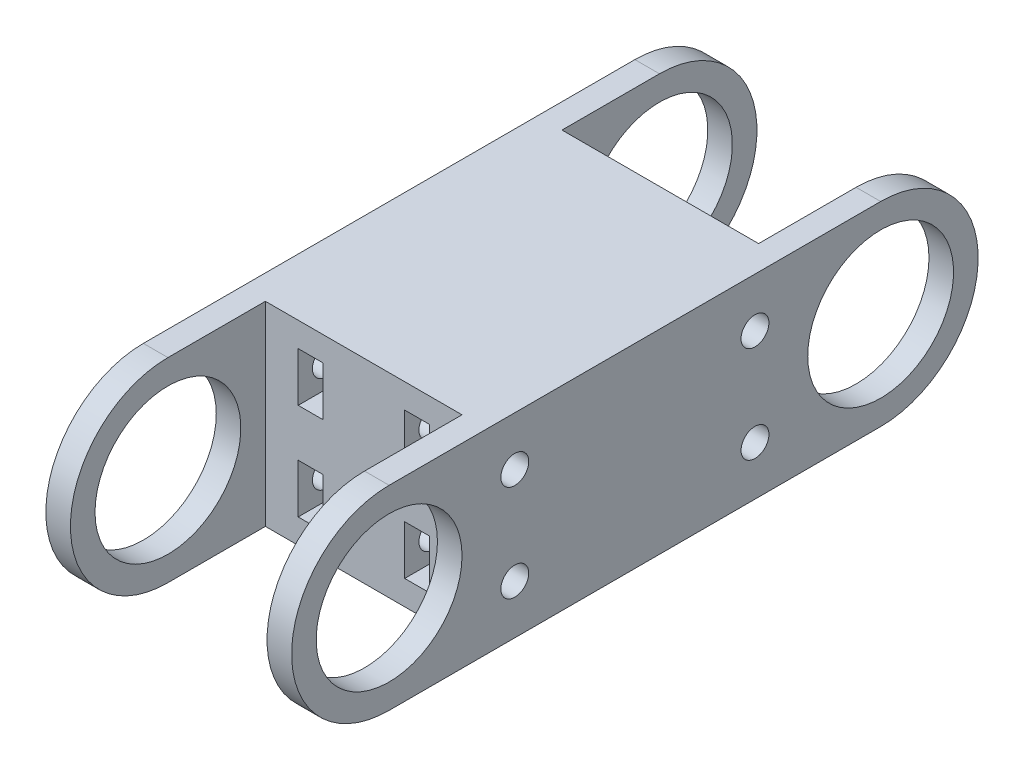
SolidWorks part; units mm, degrees
ref_plane "Front Plane" through (0, 0, 0) normal (0, 0, 1) x (1, 0, 0)
ref_plane "Top Plane" through (0, 0, 0) normal (0, 1, 0) x (1, 0, 0)
ref_plane "Right Plane" through (0, 0, 0) normal (1, 0, 0) x (0, 0, -1)
sketch "Sketch1" plane through (0, 0, 0) normal (1, 0, 0) x (0, 0, -1)
  line L0 (0, 11.9) -> (60, 11.9)
  line L1 (0, -11.9) -> (60, -11.9)
  line L2 (30, 11.9) -> (30, -11.9) construction
  circle A0 centre (0, 0) radius 8.9
  arc A1 (0, 11.9) -> (0, -11.9) centre (0, 0) ccw
  circle A2 centre (60, 0) radius 8.9
  arc A3 (60, 11.9) -> (60, -11.9) centre (60, 0) cw
  point P13 (63.6944, 11.9)
  dimension "D1" = 17.8
  dimension "D2" = 23.8
  dimension "D3" = 60
extrude "Boss-Extrude1" add sketch "Sketch1" along normal blind 30
sketch "Sketch2" plane through (0, 11.9, 0) normal (0, 1, 0) x (1, 0, 0)
  line L0 (0, -11.9) -> (30, -11.9) construction
  line L1 (3, -11.9) -> (27, -11.9)
  line L2 (3, -11.9) -> (3, 11.9)
  line L3 (3, 11.9) -> (27, 11.9)
  line L4 (27, -11.9) -> (27, 11.9)
  line L5 (0, 30) -> (30, 30) construction
  line L6 (0, 60) -> (0, 0) construction
  line L7 (30, 60) -> (30, 0) construction
  line L8 (3, 48.1) -> (27, 48.1)
  line L9 (27, 71.9) -> (27, 48.1)
  line L10 (3, 71.9) -> (27, 71.9)
  line L11 (3, 71.9) -> (3, 48.1)
  dimension "D1" = 23.8
  dimension "D2" = 3
  dimension "D3" = 3
extrude "Cut-Extrude1" cut sketch "Sketch2" against normal through all
hole_wizard "M3 Clearance Hole1" positions "3DSketch1" profile "Sketch3" hole size "M3" standard "ANSI Metric" end condition through all
sketch3d "3DSketch1"
  circle A0 centre (32.975, -5.9, -15.34) radius 1.7 construction
  circle A1 centre (32.975, 5.9, -15.34) radius 1.7 construction
  circle A2 centre (32.975, 5.9, -44.66) radius 1.7 construction
  circle A3 centre (32.975, -5.9, -44.66) radius 1.7 construction
  point P0 (30, -5.9, -15.34)
  point P2 (30, 5.9, -15.34)
  point P4 (30, 5.9, -44.66)
  point P6 (30, -5.9, -44.66)
  point P9 (0, 0, 0)
  point P12 (34.675, -5.9, -15.34)
  point P13 (0, 0, 0)
  point P16 (34.675, 5.9, -15.34)
  point P17 (0, 0, 0)
  point P20 (34.675, 5.9, -44.66)
  point P21 (0, 0, 0)
  point P24 (34.675, -5.9, -44.66)
sketch "Sketch3" plane through (30, -5.9, -15.34) normal (0, 1, 0) x (0, 0, -1)
  line L0 (0, 0) -> (0, 30)
  line L1 (0, 30) -> (1.7, 30)
  line L2 (1.7, 30) -> (1.7, 0)
  line L5 (1.7, 0) -> (0, 0)
  line L11 (0, -6.35) -> (0, 107.95) construction
  dimension "Thru Hole Dia." = 3.4
  dimension "Thru Hole Depth" = 30
sketch "Sketch4" plane through (0, 0, -48.1) normal (0, 0, -1) x (-1, 0, 0)
  line L1 (-23, -2.9) -> (-20, -2.9)
  line L2 (-23, -2.9) -> (-23, -8.9)
  line L3 (-23, -8.9) -> (-20, -8.9)
  line L4 (-20, -2.9) -> (-20, -8.9)
  line L7 (-30, -4.2) -> (-30, -7.6) construction
  line L8 (-30, -4.2) -> (-30, -7.6) construction
  line L9 (-27, -11.9) -> (-27, 11.9) construction
  line L10 (-15, -11.9) -> (-15, 11.9) construction
  line L11 (-3, -11.9) -> (-27, -11.9) construction
  line L12 (-3, 11.9) -> (-27, 11.9) construction
  line L13 (-27, 0) -> (-3, 0) construction
  line L14 (-3, -11.9) -> (-3, 11.9) construction
  line L15 (-23, 8.9) -> (-20, 8.9)
  line L16 (-20, 2.9) -> (-20, 8.9)
  line L17 (-23, 2.9) -> (-20, 2.9)
  line L18 (-23, 2.9) -> (-23, 8.9)
  line L19 (-7, -8.9) -> (-10, -8.9)
  line L20 (-10, -2.9) -> (-10, -8.9)
  line L21 (-7, -2.9) -> (-10, -2.9)
  line L22 (-7, -2.9) -> (-7, -8.9)
  line L23 (-7, 2.9) -> (-7, 8.9)
  line L24 (-7, 2.9) -> (-10, 2.9)
  line L25 (-10, 2.9) -> (-10, 8.9)
  line L26 (-7, 8.9) -> (-10, 8.9)
  point P6 (-23, -5.9)
  point P7 (-30, -5.9)
  dimension "D1" = 3
  dimension "D2" = 6
  dimension "D3" = 4
extrude "Cut-Extrude2" cut sketch "Sketch4" against normal blind 6.19
ref_plane "Plane1" through (0, 0, -30) normal (0, 0, 1) x (1, 0, 0)
mirror "Mirror1" about plane through (0, 0, -30) normal (0, 0, 1) of "Cut-Extrude2"
